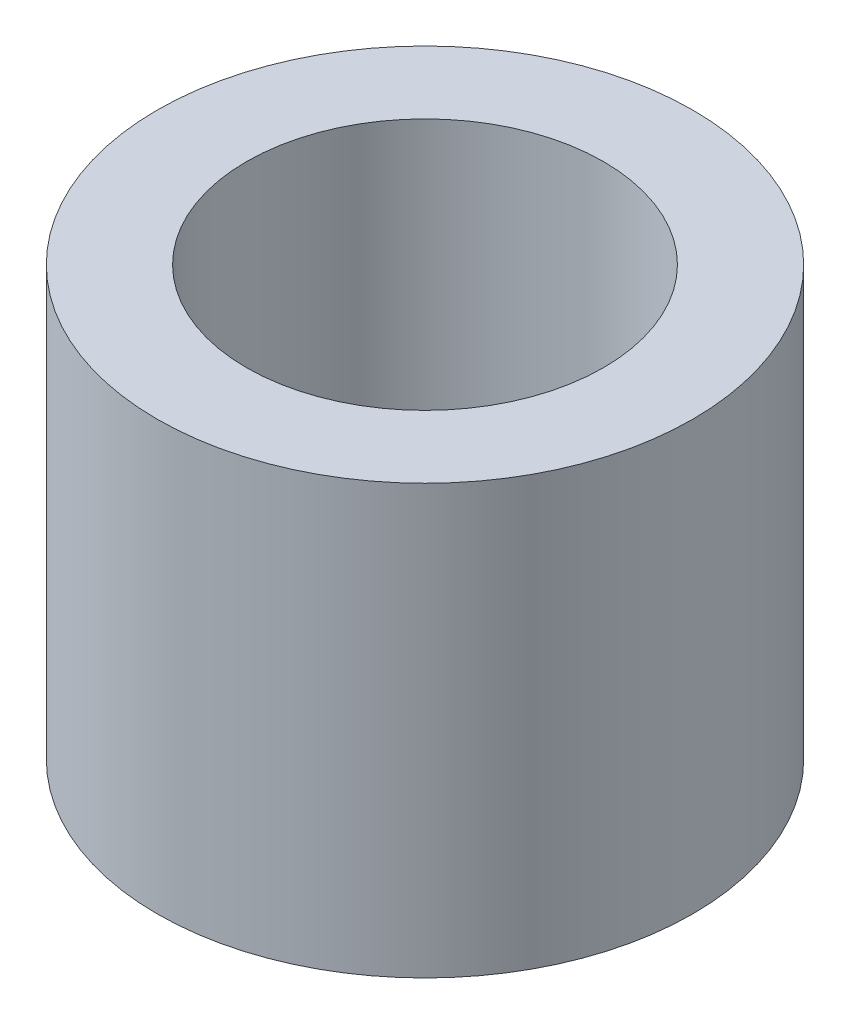
SolidWorks part; units mm, degrees
ref_plane "Front Plane" through (0, 0, 0) normal (0, 0, 1) x (1, 0, 0)
ref_plane "Top Plane" through (0, 0, 0) normal (0, 1, 0) x (1, 0, 0)
ref_plane "Right Plane" through (0, 0, 0) normal (1, 0, 0) x (0, 0, -1)
sketch "Sketch2" plane through (0, 0, 0) normal (0, 1, 0) x (1, 0, 0)
  circle A0 centre (0, 0) radius 5
  circle A1 centre (0, 0) radius 7.5
  dimension "D1" = 5
  dimension "D2" = 7.5
extrude "Boss-Extrude1" add sketch "Sketch2" along normal blind 12
